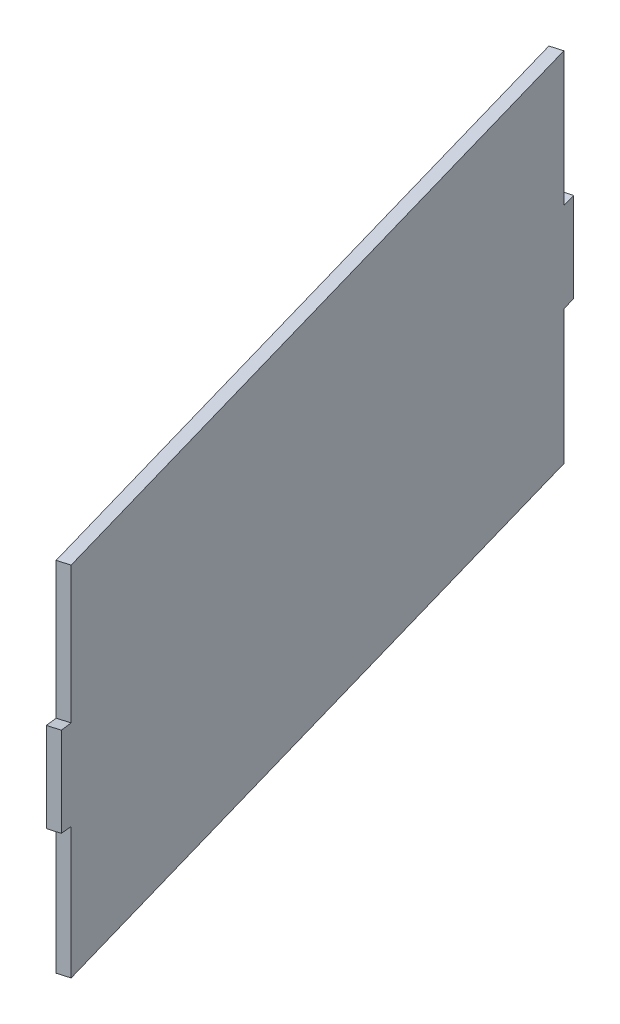
SolidWorks part; units mm, degrees
ref_plane "Front Plane" through (0, 0, 0) normal (0, 0, 1) x (1, 0, 0)
ref_plane "Top Plane" through (0, 0, 0) normal (0, 1, 0) x (1, 0, 0)
ref_plane "Right Plane" through (0, 0, 0) normal (1, 0, 0) x (0, 0, -1)
sketch "Sketch1" plane through (972.2876, 0, -279.7619) normal (0.961, 0, -0.2765) x (-0.2765, 0, -0.961)
  line L3 (2602.3302, -41.5816) -> (1998.3451, -41.5816)
  line L4 (1998.3451, -41.5816) -> (1998.3451, -156.2542)
  line L5 (2055.5834, -41.5816) -> (1998.3451, -41.5816) construction
  line L6 (1998.3451, -41.5816) -> (1998.3451, -341.5816) construction
  line L7 (2614.3302, -154.0816) -> (2614.3302, -229.0816)
  line L8 (2614.3302, -229.0816) -> (2602.3302, -229.0816)
  line L9 (2602.3302, -229.0816) -> (2602.3302, -341.5816)
  line L10 (2602.3302, -341.5816) -> (1998.3451, -341.5816)
  line L11 (2737.7791, -154.0816) -> (1998.3451, -154.0816) construction
  line L12 (2300.3376, -341.5816) -> (2300.3376, -41.5816) construction
  line L13 (1986.3451, -229.0816) -> (1998.3451, -231.5124)
  line L14 (1986.3451, -154.0816) -> (1986.3451, -229.0816)
  line L15 (1986.3451, -154.0816) -> (1998.3451, -156.2542)
  line L16 (1998.3451, -231.5124) -> (1998.3451, -341.5816)
  line L17 (2602.3302, -41.5816) -> (2602.3302, -154.0816)
  line L18 (2737.7791, -154.0816) -> (2737.7791, -229.0816) construction
  line L20 (2602.3302, -154.0816) -> (2614.3302, -154.0816)
  line L21 (2602.3302, -154.0816) -> (2602.3302, -229.0816) construction
  dimension "D1" = 12
  dimension "D2" = 75
extrude "Boss-Extrude1" add sketch "Sketch1" against normal blind 10.16
